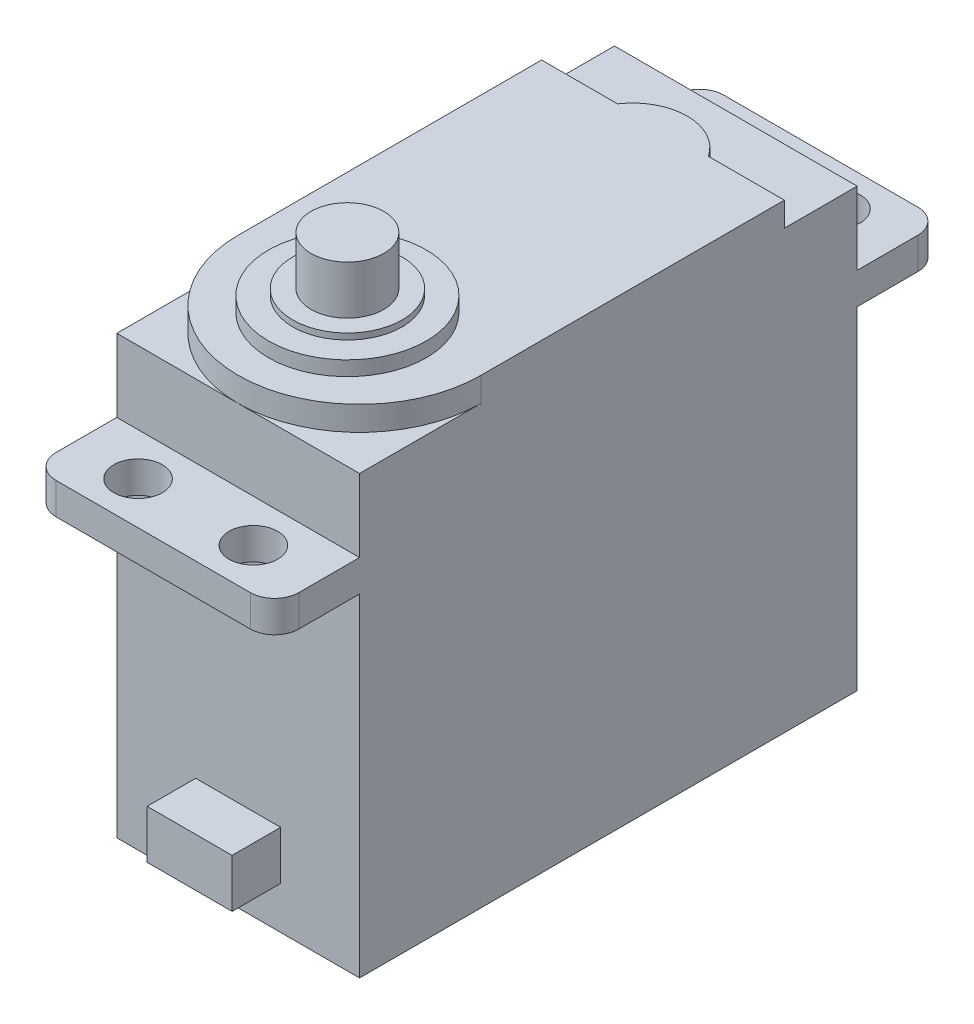
SolidWorks part; units mm, degrees
ref_plane "Ebene vorne" through (0, 0, 0) normal (0, 0, 1) x (1, 0, 0)
ref_plane "Ebene oben" through (0, 0, 0) normal (0, 1, 0) x (1, 0, 0)
ref_plane "Ebene rechts" through (0, 0, 0) normal (1, 0, 0) x (0, 0, -1)
sketch "Skizze1" plane through (0, 0, 0) normal (1, 0, 0) x (0, 0, -1)
  line L0 (-11.0147, 22.7521) -> (-11.0147, 28.7521)
  line L1 (-11.0147, -7.2479) -> (29.9853, -7.2479)
  line L2 (-11.0147, -7.2479) -> (-11.0147, 20.1521)
  line L4 (29.9853, -7.2479) -> (29.9853, 20.1521)
  line L5 (-11.0147, 22.7521) -> (-18.0147, 22.7521)
  line L7 (-11.0147, 20.1521) -> (-18.0147, 20.1521)
  line L8 (-18.0147, 22.7521) -> (-18.0147, 20.1521)
  line L9 (29.9853, 22.7521) -> (36.9853, 22.7521)
  line L11 (29.9853, 20.1521) -> (36.9853, 20.1521)
  line L12 (36.9853, 22.7521) -> (36.9853, 20.1521)
  line L17 (29.9853, 22.7521) -> (29.9853, 28.7521)
  line L18 (-11.0147, 28.7521) -> (29.9853, 28.7521)
  dimension "D1" = 41
  dimension "D2" = 2.6
  dimension "D3" = 6
  dimension "D4" = 2.6
  dimension "D5" = 7
  dimension "D6" = 7
  dimension "36" = 36
extrude "Aufsatz-Linear austragen3" add sketch "Skizze1" along normal blind 20
ref_plane "Ebene1" through (0, 0, -9.4853) normal (0, 0, -1) x (-1, 0, 0)
sketch "Skizze2" plane through (0, 28.7521, 0) normal (0, 1, 0) x (1, 0, 0)
  line L0 (20, -11.0147) -> (0, -11.0147) construction
  line L1 (0, 29.9853) -> (0, -11.0147) construction
  line L2 (20, 29.9853) -> (20, -11.0147) construction
  line L4 (0, -1.0147) -> (0, 23.9853)
  line L5 (0, 23.9853) -> (6.2583, 23.9853)
  line L6 (20, -1.0147) -> (20, 23.9853)
  line L7 (20, 29.9853) -> (0, 29.9853) construction
  line L8 (13.7417, 23.9853) -> (20, 23.9853)
  arc A0 (0, -1.0147) -> (20, -1.0147) centre (10, -1.0147) ccw
  arc A1 (13.7417, 23.9853) -> (6.2583, 23.9853) centre (10, 21.4853) ccw
  dimension "D1" = 20
  dimension "D5" = 2.5
  dimension "D6" = 9
  dimension "D2" = 10
  dimension "D3" = 10
  dimension "D4" = 6
  dimension "D7" = 10
extrude "Aufsatz-Linear austragen4" add sketch "Skizze2" along normal blind 2
sketch "Skizze3" plane through (0, 30.7521, 0) normal (0, 1, 0) x (1, 0, 0)
  line L0 (0, 29.9853) -> (0, 23.9853) construction
  line L1 (20, -11.0147) -> (10, -11.0147) construction
  circle A0 centre (10, -2.0147) radius 6.5
  dimension "D1" = 13
  dimension "D2" = 10
  dimension "D3" = 9
extrude "Aufsatz-Linear austragen5" add sketch "Skizze3" along normal blind 1.2
sketch "Skizze4" plane through (0, 22.7521, 0) normal (0, 1, 0) x (1, 0, 0)
  line L0 (5.25, -14.5147) -> (14.75, -14.5147) construction
  line L1 (20, -11.0147) -> (20, -18.0147) construction
  line L2 (11, 9.4853) -> (-11, 9.4853) construction
  line L3 (20, -11.0147) -> (0, -11.0147) construction
  circle A0 centre (5.25, -14.5147) radius 2
  circle A1 centre (14.75, -14.5147) radius 2
  circle A2 centre (14.75, 33.4853) radius 2
  circle A3 centre (5.25, 33.4853) radius 2
  dimension "D1" = 4
  dimension "D2" = 9.5
  dimension "D3" = 5.25
  dimension "D4" = 3.5
extrude "Schnitt-Linear austragen1" cut sketch "Skizze4" against normal up to next
sketch "Skizze6" plane through (0, 0, 11.0147) normal (0, 0, 1) x (1, 0, 0)
  line L0 (20, -7.2479) -> (0, -7.2479) construction
  line L1 (6.5, -3.7479) -> (13.5, -3.7479)
  line L2 (6.5, -3.7479) -> (6.5, 0.2521)
  line L3 (6.5, 0.2521) -> (13.5, 0.2521)
  line L4 (13.5, -3.7479) -> (13.5, 0.2521)
  line L5 (0, 28.7521) -> (0, 22.7521) construction
  dimension "D1" = 7
  dimension "D2" = 3.5
  dimension "4" = 4
  dimension "6,5" = 6.5
extrude "Aufsatz-Linear austragen6" add sketch "Skizze6" along normal blind 4
sketch "Skizze7" plane through (0, 31.9521, 0) normal (0, 1, 0) x (1, 0, 0)
  line L0 (0, 23.9853) -> (0, -1.0147) construction
  line L1 (20, -11.0147) -> (10, -11.0147) construction
  circle A0 centre (10, -2.0147) radius 4.5
  dimension "D1" = 10
  dimension "D2" = 9
extrude "Aufsatz-Linear austragen7" add sketch "Skizze7" along normal blind 0.5
sketch "Skizze8" plane through (0, 32.4521, 0) normal (0, 1, 0) x (1, 0, 0)
  line L0 (10, -11.0147) -> (0, -11.0147) construction
  line L1 (20, -1.0147) -> (20, 23.9853) construction
  circle A0 centre (10, -2.0147) radius 3
  point P6 (12.9049, -3.2933)
  point P9 (0, 0)
  dimension "D1" = 6
  dimension "D2" = 9
  dimension "D3" = 10
extrude "Aufsatz-Linear austragen8" add sketch "Skizze8" along normal blind 4
fillet "Verrundung3" radius 2 4 edges at (0, 21.4521, -36.9853) (20, 21.4521, -36.9853) (20, 21.4521, 18.0147) (0, 21.4521, 18.0147)
